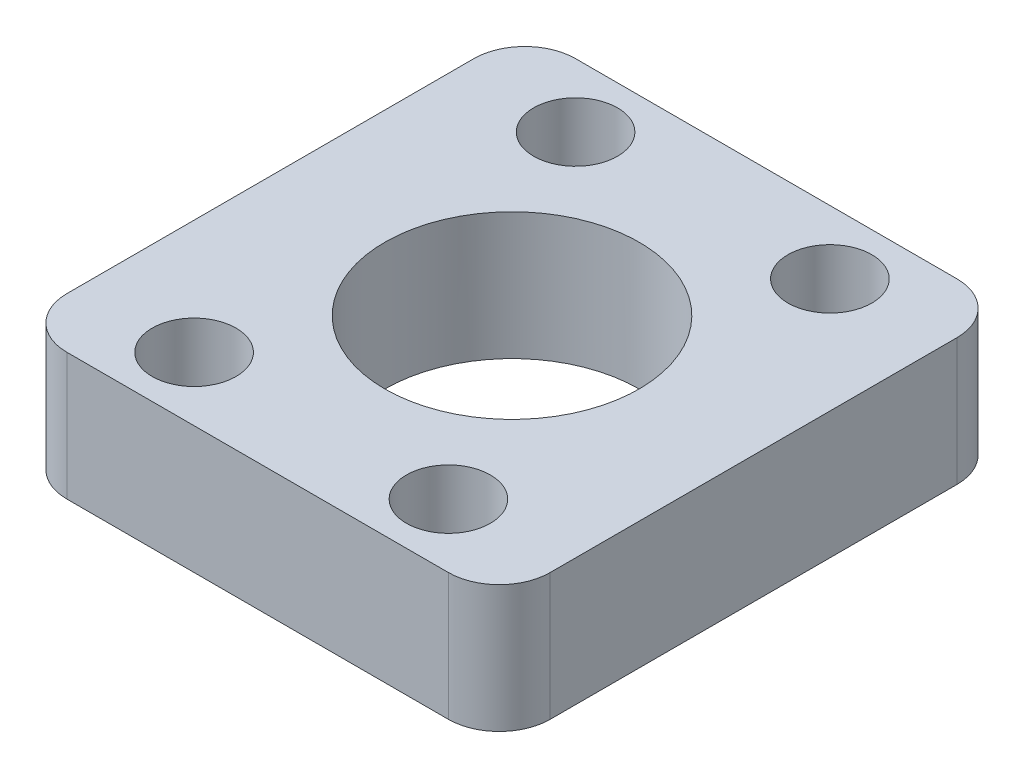
SolidWorks part; units mm, degrees
ref_plane "Front" through (0, 0, 0) normal (0, 0, 1) x (1, 0, 0)
ref_plane "Top" through (0, 0, 0) normal (0, 1, 0) x (1, 0, 0)
ref_plane "Right" through (0, 0, 0) normal (1, 0, 0) x (0, 0, -1)
sketch "草图1" plane through (0, 0, 0) normal (0, 1, 0) x (1, 0, 0)
  line L1 (-9.5, -10) -> (9.5, -10)
  line L2 (-9.5, -10) -> (-9.5, 10)
  line L3 (-9.5, 10) -> (9.5, 10)
  line L4 (9.5, -10) -> (9.5, 10)
  line L5 (-9.5, -10) -> (9.5, 10) construction
  line L6 (-9.5, 10) -> (9.5, -10) construction
  point P0 (0, 0)
  dimension "D1" = 19
  dimension "D2" = 20
extrude "凸台-拉伸1" add sketch "草图1" along normal blind 5
sketch "草图2" plane through (0, 5, 0) normal (0, 1, 0) x (1, 0, 0)
  line L0 (-11.0086, 0) -> (13.9788, 0) construction
  line L1 (-5, 7.5) -> (-9.5, 7.5) construction
  line L2 (-9.5, 10) -> (-9.5, -10) construction
  line L3 (5, 7.5) -> (9.5, 7.5) construction
  line L4 (9.5, -10) -> (9.5, 10) construction
  line L5 (5, -7.5) -> (9.5, -7.5) construction
  line L6 (-5, -7.5) -> (-9.5, -7.5) construction
  circle A0 centre (-5, 7.5) radius 1.65
  circle A1 centre (5, 7.5) radius 1.65
  circle A2 centre (5, -7.5) radius 1.65
  circle A3 centre (-5, -7.5) radius 1.65
  dimension "D1" = 3.3
  dimension "D2" = 3.3
  dimension "D3" = 10
  dimension "D4" = 7.5
extrude "切除-拉伸1" cut sketch "草图2" against normal through all
fillet "圆角1" radius 2 4 edges at (9.5, 2.5, -10) (9.5, 2.5, 10) (-9.5, 2.5, 10) (-9.5, 2.5, -10)
sketch "草图3" plane through (0, 5, 0) normal (0, 1, 0) x (1, 0, 0)
  circle A0 centre (0, 0) radius 5
  dimension "D1" = 10
extrude "切除-拉伸2" cut sketch "草图3" against normal blind 10
